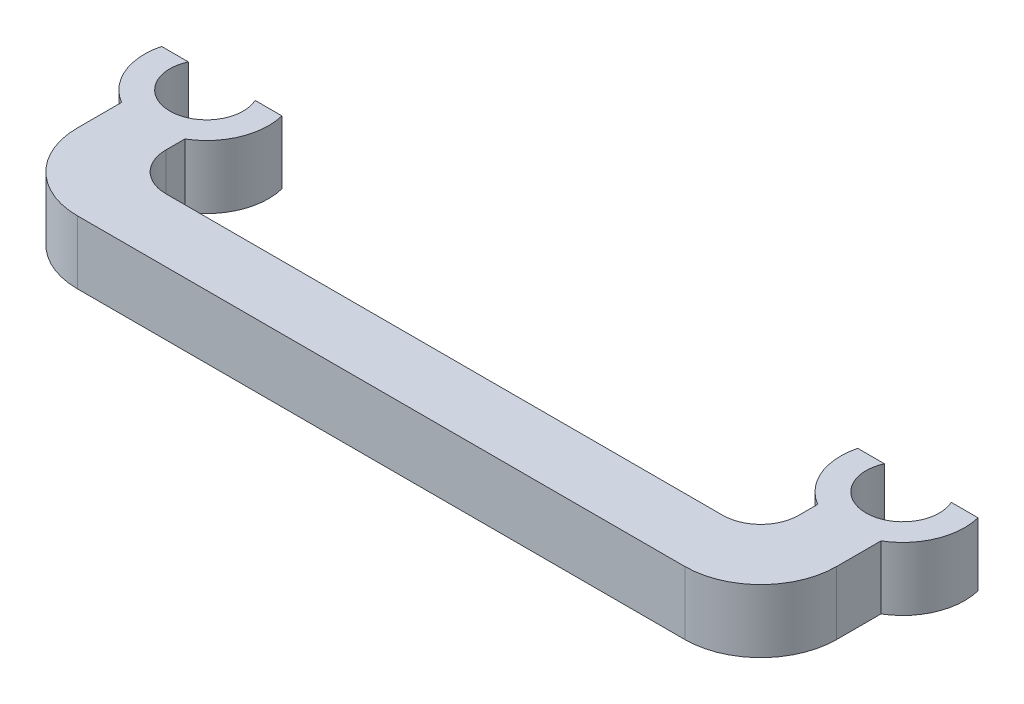
SolidWorks part; units mm, degrees
material "ABS PC"
ref_plane "Front Plane" through (0, 0, 0) normal (0, 0, 1) x (1, 0, 0)
ref_plane "Top Plane" through (0, 0, 0) normal (0, 1, 0) x (1, 0, 0)
ref_plane "Right Plane" through (0, 0, 0) normal (1, 0, 0) x (0, 0, -1)
sketch "Sketch2" plane through (0, 0, 0) normal (0, 1, 0) x (1, 0, 0)
  line L0 (0, 2.5) -> (0, -2.5) construction
  line L1 (25, 2.5) -> (-25, 2.5)
  line L2 (30, -2.5) -> (-30, -2.5)
  line L3 (-30.1401, 12.4143) -> (-24.8599, 12.4143) construction
  line L4 (-30.1401, 12.4143) -> (-32.2508, 12.4143)
  line L5 (-27.5, 12.4143) -> (-27.5, 5.8024) construction
  line L6 (-24.8599, 12.4143) -> (-22.7492, 12.4143)
  line L7 (-30, 7) -> (-30, -2.5)
  line L8 (-25, 7) -> (-25, 2.5)
  line L9 (-25, 5.8024) -> (-30, 5.8024) construction
  line L10 (25, 5.8024) -> (30, 5.8024) construction
  line L11 (27.5, 12.4143) -> (27.5, 5.8024) construction
  line L12 (30.1401, 12.4143) -> (24.8599, 12.4143) construction
  line L13 (25, 7) -> (25, 2.5)
  line L14 (30, 7) -> (30, -2.5)
  line L15 (24.8599, 12.4143) -> (22.7492, 12.4143)
  line L16 (30.1401, 12.4143) -> (32.2508, 12.4143)
  arc A0 (-30.1401, 12.4143) -> (-24.8599, 12.4143) centre (-27.5, 11.2143) ccw
  arc A1 (-32.2508, 12.4143) -> (-22.7492, 12.4143) centre (-27.5, 11.2143) ccw
  arc A2 (32.2508, 12.4143) -> (22.7492, 12.4143) centre (27.5, 11.2143) cw
  arc A3 (30.1401, 12.4143) -> (24.8599, 12.4143) centre (27.5, 11.2143) cw
  point P4 (-26.1905, 5.8024)
  point P17 (-27.5, 5.8024)
  point P18 (-27.9504, 5.8024)
  point P32 (27.5, 5.8024)
  dimension "D1" = 5
  dimension "D2" = 2.9
  dimension "D4" = 2
  dimension "D3" = 1.2
  dimension "D5" = 5
  dimension "D6" = 55
  dimension "D7" = 4.5
extrude "Boss-Extrude1" add sketch "Sketch2" along normal blind 5 contours A1 L6 A0 L4 | L14 A2 L13 L1 L8 A1 L7 L2 | L16 A3 L15 A2
fillet "Fillet1" radius 3 2 edges at (25, 2.5, -2.5) (-25, 2.5, -2.5)
fillet "Fillet2" radius 6 2 edges at (30, 2.5, 2.5) (-30, 2.5, 2.5)
